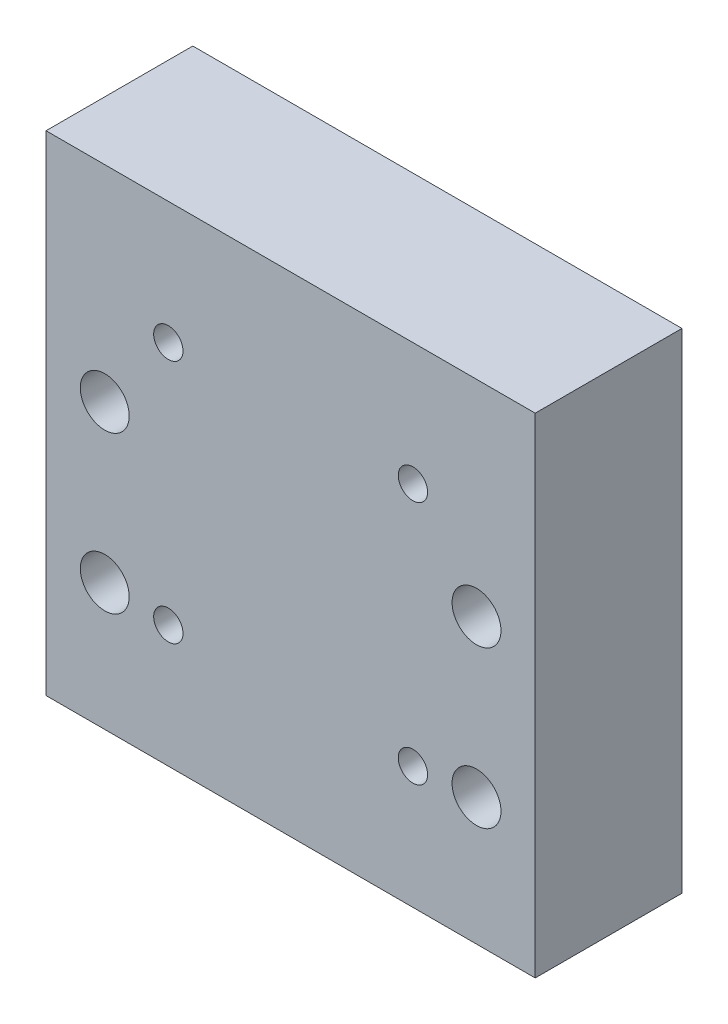
SolidWorks part; units mm, degrees
ref_plane "Front Plane" through (0, 0, 0) normal (0, 0, 1) x (1, 0, 0)
ref_plane "Top Plane" through (0, 0, 0) normal (0, 1, 0) x (1, 0, 0)
ref_plane "Right Plane" through (0, 0, 0) normal (1, 0, 0) x (0, 0, -1)
sketch "Sketch1" plane through (0, 0, 0) normal (0, 0, 1) x (1, 0, 0)
  line L1 (-25, -25) -> (25, -25)
  line L2 (-25, -25) -> (-25, 25)
  line L3 (-25, 25) -> (25, 25)
  line L4 (25, -25) -> (25, 25)
  line L5 (-25, -25) -> (25, 25) construction
  line L6 (-25, 25) -> (25, -25) construction
  point P0 (0, 0)
  dimension "D1" = 50
  dimension "D2" = 50
extrude "Boss-Extrude1" add sketch "Sketch1" along normal blind 15
sketch "Sketch2" plane through (0, 0, 0) normal (0, 0, -1) x (-1, 0, 0)
  line L0 (0, 25) -> (0, -25) construction
  line L1 (-25, 25) -> (25, 25) construction
  line L2 (25, -25) -> (-25, -25) construction
  line L3 (-19, 25) -> (-19, -25) construction
  circle A0 centre (-19, 4) radius 1.5
  circle A1 centre (-19, -12) radius 1.5
  circle A2 centre (19, -12) radius 1.5
  circle A3 centre (19, 4) radius 1.5
  dimension "D1" = 3
  dimension "D2" = 38
  dimension "D3" = 16
  dimension "D4" = 13
extrude "Cut-Extrude1" cut sketch "Sketch2" against normal up to next
sketch "Sketch3" plane through (0, 0, 15) normal (0, 0, 1) x (1, 0, 0)
  line L0 (0, 25) -> (0, -25) construction
  line L1 (25, 25) -> (-25, 25) construction
  line L2 (-25, -25) -> (25, -25) construction
  circle A0 centre (-19, 4) radius 2.5
  circle A1 centre (-19, -12) radius 2.5
  circle A2 centre (19, 4) radius 2.5
  circle A3 centre (19, -12) radius 2.5
  dimension "D1" = 5
extrude "Cut-Extrude2" cut sketch "Sketch3" against normal blind 5
sketch "Sketch4" plane through (0, 0, 15) normal (0, 0, 1) x (1, 0, 0)
  line L0 (0, -25) -> (0, 25) construction
  line L1 (-25, -25) -> (25, -25) construction
  line L2 (25, 25) -> (-25, 25) construction
  line L3 (-12.5, 25) -> (-12.5, -25) construction
  line L4 (12.5, 25) -> (12.5, -25) construction
  circle A0 centre (-12.5, -12.5) radius 1.5
  circle A1 centre (-12.5, 12.5) radius 1.5
  circle A2 centre (12.5, -12.5) radius 1.5
  circle A3 centre (12.5, 12.5) radius 1.5
  dimension "D4" = 3
  dimension "D5" = 3
  dimension "D1" = 25
  dimension "D2" = 25
  dimension "D3" = 12.5
extrude "Cut-Extrude3" cut sketch "Sketch4" against normal up to next
